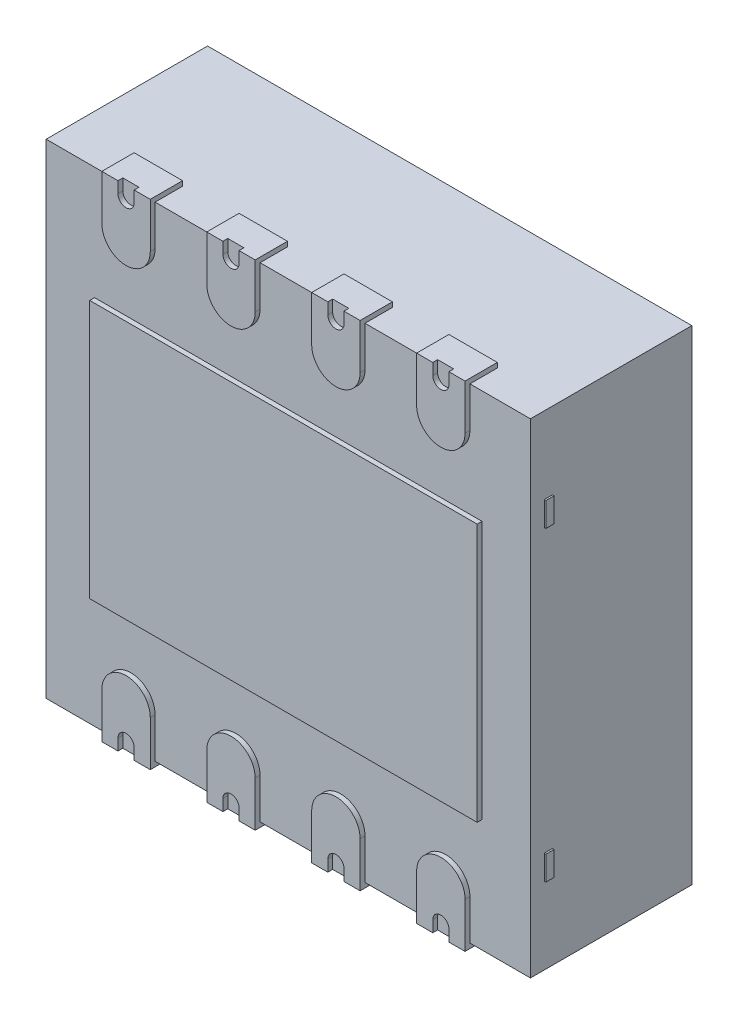
SolidWorks part; units mm, degrees
ref_plane "Front Plane" through (0, 0, 0) normal (0, 0, 1) x (1, 0, 0)
ref_plane "Top Plane" through (0, 0, 0) normal (0, 1, 0) x (1, 0, 0)
ref_plane "Right Plane" through (0, 0, 0) normal (1, 0, 0) x (0, 0, -1)
sketch "Sketch1" plane through (0, 0, 0) normal (0, 0, 1) x (1, 0, 0)
  line L1 (1.5, 1.5) -> (-1.5, 1.5)
  line L2 (1.5, 1.5) -> (1.5, -1.5)
  line L3 (1.5, -1.5) -> (-1.5, -1.5)
  line L4 (-1.5, 1.5) -> (-1.5, -1.5)
  line L5 (1.5, 1.5) -> (-1.5, -1.5) construction
  line L6 (1.5, -1.5) -> (-1.5, 1.5) construction
  point P0 (0, 0)
  dimension "D1" = 3
  dimension "D2" = 3
extrude "Boss-Extrude1" add sketch "Sketch1" against normal blind 1
sketch "Sketch2" plane through (0, 0, 0) normal (0, 0, 1) x (-1, 0, 0)
  line L0 (-0.975, 1.25) -> (-0.975, 1.6035) construction
  line L1 (1.2, 0.8) -> (-1.2, 0.8)
  line L2 (1.2, 0.8) -> (1.2, -0.8)
  line L3 (1.2, -0.8) -> (-1.2, -0.8)
  line L4 (-1.2, 0.8) -> (-1.2, -0.8)
  line L5 (1.2, 0.8) -> (-1.2, -0.8) construction
  line L6 (1.2, -0.8) -> (-1.2, 0.8) construction
  line L7 (-1.125, 1.25) -> (-1.125, 1.6035)
  line L8 (-0.825, 1.25) -> (-0.825, 1.6035)
  line L9 (1.5, 1.5) -> (-1.5, 1.5) construction
  line L10 (-0.175, 1.25) -> (-0.175, 1.6035)
  line L11 (-0.475, 1.25) -> (-0.475, 1.6035)
  line L12 (-0.325, 1.25) -> (-0.325, 1.6035) construction
  line L13 (0.475, 1.25) -> (0.475, 1.6035)
  line L14 (0.175, 1.25) -> (0.175, 1.6035)
  line L15 (0.325, 1.25) -> (0.325, 1.6035) construction
  line L16 (1.125, 1.25) -> (1.125, 1.6035)
  line L17 (0.825, 1.25) -> (0.825, 1.6035)
  line L18 (0.975, 1.25) -> (0.975, 1.6035) construction
  line L19 (0, 0) -> (0.825, 0) construction
  line L20 (-0.975, -1.25) -> (-0.975, -1.6035) construction
  line L21 (-1.125, -1.25) -> (-1.125, -1.6035)
  line L22 (-0.825, -1.25) -> (-0.825, -1.6035)
  line L23 (-0.325, -1.25) -> (-0.325, -1.6035) construction
  line L24 (-0.475, -1.25) -> (-0.475, -1.6035)
  line L25 (-0.175, -1.25) -> (-0.175, -1.6035)
  line L26 (0.325, -1.25) -> (0.325, -1.6035) construction
  line L27 (0.175, -1.25) -> (0.175, -1.6035)
  line L28 (0.475, -1.25) -> (0.475, -1.6035)
  line L29 (0.975, -1.25) -> (0.975, -1.6035) construction
  line L30 (0.825, -1.25) -> (0.825, -1.6035)
  line L31 (1.125, -1.25) -> (1.125, -1.6035)
  arc A0 (-1.125, 1.25) -> (-0.825, 1.25) centre (-0.975, 1.25) ccw
  arc A1 (-0.825, 1.6035) -> (-1.125, 1.6035) centre (-0.975, 1.6035) ccw
  arc A2 (-0.475, 1.25) -> (-0.175, 1.25) centre (-0.325, 1.25) ccw
  arc A3 (-0.175, 1.6035) -> (-0.475, 1.6035) centre (-0.325, 1.6035) ccw
  arc A4 (0.175, 1.25) -> (0.475, 1.25) centre (0.325, 1.25) ccw
  arc A5 (0.475, 1.6035) -> (0.175, 1.6035) centre (0.325, 1.6035) ccw
  arc A6 (0.825, 1.25) -> (1.125, 1.25) centre (0.975, 1.25) ccw
  arc A7 (1.125, 1.6035) -> (0.825, 1.6035) centre (0.975, 1.6035) ccw
  arc A8 (-1.125, -1.25) -> (-0.825, -1.25) centre (-0.975, -1.25) cw
  arc A9 (-0.825, -1.6035) -> (-1.125, -1.6035) centre (-0.975, -1.6035) cw
  arc A10 (-0.475, -1.25) -> (-0.175, -1.25) centre (-0.325, -1.25) cw
  arc A11 (-0.175, -1.6035) -> (-0.475, -1.6035) centre (-0.325, -1.6035) cw
  arc A12 (0.175, -1.25) -> (0.475, -1.25) centre (0.325, -1.25) cw
  arc A13 (0.475, -1.6035) -> (0.175, -1.6035) centre (0.325, -1.6035) cw
  arc A14 (0.825, -1.25) -> (1.125, -1.25) centre (0.975, -1.25) cw
  arc A15 (1.125, -1.6035) -> (0.825, -1.6035) centre (0.975, -1.6035) cw
  point P0 (0, 0)
  point P8 (-0.975, 1.4268)
  point P13 (-0.975, 1.1)
  point P19 (-0.325, 1.4268)
  point P26 (0.325, 1.4268)
  point P33 (0.975, 1.4268)
  point P41 (-0.975, -1.4268)
  point P48 (-0.325, -1.4268)
  point P55 (0.325, -1.4268)
  point P62 (0.975, -1.4268)
  dimension "D1" = 1.6
  dimension "D2" = 2.4
  dimension "D3" = 0.3
  dimension "D4" = 0.4
  dimension "D5" = 0.975
  dimension "D6" = 4
extrude "Boss-Extrude2" add sketch "Sketch2" along normal blind 0.03
sketch "Sketch4" plane through (0, 0, -1) normal (0, 0, -1) x (-1, 0, 0)
  line L1 (1.5, 1.5) -> (-1.5, 1.5)
  line L2 (1.5, 1.5) -> (1.5, -1.5)
  line L3 (1.5, -1.5) -> (-1.5, -1.5)
  line L4 (-1.5, 1.5) -> (-1.5, -1.5)
  line L5 (-2.0468, 1.8988) -> (1.8937, 1.8988)
  line L6 (-2.0468, 1.8988) -> (-2.0468, -1.9448)
  line L7 (-2.0468, -1.9448) -> (1.8937, -1.9448)
  line L8 (1.8937, 1.8988) -> (1.8937, -1.9448)
extrude "Cut-Extrude1" cut sketch "Sketch4" against normal blind 60.05
sketch "Sketch7" plane through (0, -1.5, 0) normal (0, -1, 0) x (1, 0, 0)
  line L0 (0.825, 0.03) -> (0.825, 0) construction
  line L1 (1.125, -0.17) -> (0.825, -0.17)
  line L2 (1.125, -0.17) -> (1.125, 0.03)
  line L3 (1.125, 0.03) -> (0.825, 0.03)
  line L4 (0.825, -0.17) -> (0.825, 0.03)
  line L5 (0.175, 0.03) -> (0.175, 0) construction
  line L6 (0.475, -0.17) -> (0.175, -0.17)
  line L7 (0.475, -0.17) -> (0.475, 0.03)
  line L8 (0.475, 0.03) -> (0.175, 0.03)
  line L9 (0.175, -0.17) -> (0.175, 0.03)
  line L10 (-0.475, 0.03) -> (-0.475, 0) construction
  line L11 (-0.175, -0.17) -> (-0.475, -0.17)
  line L12 (-0.175, -0.17) -> (-0.175, 0.03)
  line L13 (-0.175, 0.03) -> (-0.475, 0.03)
  line L14 (-0.475, -0.17) -> (-0.475, 0.03)
  line L15 (-1.125, 0.03) -> (-1.125, 0) construction
  line L16 (-0.825, -0.17) -> (-1.125, -0.17)
  line L17 (-0.825, -0.17) -> (-0.825, 0.03)
  line L18 (-0.825, 0.03) -> (-1.125, 0.03)
  line L19 (-1.125, -0.17) -> (-1.125, 0.03)
  point P7 (0.825, 0.015)
  point P22 (-0.475, 0.015)
  dimension "D1" = 0
  dimension "D2" = 0
  dimension "D3" = 0
  dimension "D4" = 0
  dimension "D5" = 0.2
  dimension "D6" = 0.2
  dimension "D7" = 0.2
  dimension "D8" = 0.2
extrude "Boss-Extrude3" add sketch "Sketch7" along normal blind 0.03
mirror "Mirror1" about plane through (0, 0, 0) normal (0, 1, 0) of "Boss-Extrude3"
sketch "Sketch8" plane through (0, 0, 0.03) normal (0, 0, 1) x (-1, 0, 0)
  line L0 (-0.975, 1.6098) -> (-0.975, 1.4598) construction
  line L1 (-0.925, 1.6098) -> (-0.925, 1.4598)
  line L2 (-1.025, 1.6098) -> (-1.025, 1.4598)
  line L3 (-0.375, 1.6098) -> (-0.375, 1.4598)
  line L6 (-0.275, 1.6098) -> (-0.275, 1.4598)
  line L9 (-0.325, 1.6098) -> (-0.325, 1.4598) construction
  line L13 (0.275, 1.6098) -> (0.275, 1.4598)
  line L15 (0.375, 1.6098) -> (0.375, 1.4598)
  line L16 (0.325, 1.6098) -> (0.325, 1.4598) construction
  line L17 (0.925, 1.6098) -> (0.925, 1.4598)
  line L18 (1.025, 1.6098) -> (1.025, 1.4598)
  line L19 (0.975, 1.6098) -> (0.975, 1.4598) construction
  line L20 (0, 0) -> (0.4114, 0) construction
  line L21 (-0.975, -1.6098) -> (-0.975, -1.4598) construction
  line L22 (-0.925, -1.6098) -> (-0.925, -1.4598)
  line L23 (-1.025, -1.6098) -> (-1.025, -1.4598)
  line L24 (-0.325, -1.6098) -> (-0.325, -1.4598) construction
  line L25 (-0.275, -1.6098) -> (-0.275, -1.4598)
  line L26 (-0.375, -1.6098) -> (-0.375, -1.4598)
  line L27 (0.325, -1.6098) -> (0.325, -1.4598) construction
  line L28 (0.375, -1.6098) -> (0.375, -1.4598)
  line L29 (0.275, -1.6098) -> (0.275, -1.4598)
  line L30 (0.975, -1.6098) -> (0.975, -1.4598) construction
  line L31 (1.025, -1.6098) -> (1.025, -1.4598)
  line L32 (0.925, -1.6098) -> (0.925, -1.4598)
  arc A0 (-0.925, 1.6098) -> (-1.025, 1.6098) centre (-0.975, 1.6098) ccw
  arc A1 (-1.025, 1.4598) -> (-0.925, 1.4598) centre (-0.975, 1.4598) ccw
  arc A8 (-0.275, 1.6098) -> (-0.375, 1.6098) centre (-0.325, 1.6098) ccw
  arc A9 (-0.375, 1.4598) -> (-0.275, 1.4598) centre (-0.325, 1.4598) ccw
  arc A10 (0.375, 1.6098) -> (0.275, 1.6098) centre (0.325, 1.6098) ccw
  arc A11 (0.275, 1.4598) -> (0.375, 1.4598) centre (0.325, 1.4598) ccw
  arc A12 (1.025, 1.6098) -> (0.925, 1.6098) centre (0.975, 1.6098) ccw
  arc A13 (0.925, 1.4598) -> (1.025, 1.4598) centre (0.975, 1.4598) ccw
  arc A14 (-0.925, -1.6098) -> (-1.025, -1.6098) centre (-0.975, -1.6098) cw
  arc A15 (-1.025, -1.4598) -> (-0.925, -1.4598) centre (-0.975, -1.4598) cw
  arc A16 (-0.275, -1.6098) -> (-0.375, -1.6098) centre (-0.325, -1.6098) cw
  arc A17 (-0.375, -1.4598) -> (-0.275, -1.4598) centre (-0.325, -1.4598) cw
  arc A18 (0.375, -1.6098) -> (0.275, -1.6098) centre (0.325, -1.6098) cw
  arc A19 (0.275, -1.4598) -> (0.375, -1.4598) centre (0.325, -1.4598) cw
  arc A20 (1.025, -1.6098) -> (0.925, -1.6098) centre (0.975, -1.6098) cw
  arc A21 (0.925, -1.4598) -> (1.025, -1.4598) centre (0.975, -1.4598) cw
  point P2 (-0.975, 1.5348)
  point P11 (-0.325, 1.5348)
  point P18 (0.325, 1.5348)
  point P25 (0.975, 1.5348)
  point P32 (-0.975, -1.5348)
  point P40 (-0.325, -1.5348)
  point P47 (0.325, -1.5348)
  point P54 (0.975, -1.5348)
  dimension "D1" = 0.05
  dimension "D2" = 4
  dimension "D3" = 0.15
extrude "Cut-Extrude2" cut sketch "Sketch8" against normal blind 0.03
sketch "Sketch9" plane through (-1.5, 0, 0) normal (-1, 0, 0) x (0, 0, 1)
  line L0 (0, 0) -> (-0.4231, 0) construction
  line L1 (-0.0858, 1.0236) -> (-0.0858, 0.8736)
  line L2 (-0.0858, 1.0236) -> (-0.1358, 1.0236)
  line L3 (-0.1358, 1.0236) -> (-0.1358, 0.8736)
  line L4 (-0.0858, 0.8736) -> (-0.1358, 0.8736)
  line L5 (-0.0858, -0.8736) -> (-0.1358, -0.8736)
  line L6 (-0.1358, -1.0236) -> (-0.1358, -0.8736)
  line L7 (-0.0858, -1.0236) -> (-0.1358, -1.0236)
  line L8 (-0.0858, -1.0236) -> (-0.0858, -0.8736)
  dimension "D1" = 0.15
  dimension "D2" = 0.05
extrude "Boss-Extrude4" add sketch "Sketch9" along normal blind 0.01
mirror "Mirror2" about plane through (0, 0, 0) normal (1, 0, 0) of "Boss-Extrude4"
sketch "Sketch11" plane through (0, 0, -1) normal (0, 0, -1) x (-1, 0, 0)
  line L0 (70.7212, 256.2979) -> (518.7212, 256.2979) construction
  line L54 (-0.8059, 1.0381) -> (-0.4233, 0.6054)
  line L55 (-0.3623, 0.9997) -> (-0.1188, 0.9997)
  line L56 (0.473, 0.2478) -> (0.2316, 0.2478)
  line L57 (-0.4233, 1.0381) -> (-0.0972, 1.0381)
  line L58 (-0.7882, 0.654) -> (-0.7882, 0.2148)
  line L59 (-0.1188, 0.9997) -> (0.0552, 0.7211)
  line L60 (-0.0933, 0.2106) -> (-0.3961, 0.2106)
  line L61 (-0.7882, 0.2148) -> (-1.0676, 0.2148)
  line L62 (0.5173, 0.9997) -> (0.9108, 0.9942)
  line L63 (0.5012, 0.8902) -> (0.5012, 0.6704)
  line L64 (0.9437, 0.5264) -> (0.5435, 0.5264)
  line L65 (-1.0282, 0.2545) -> (-1.0282, 0.9912)
  line L66 (0.5397, 0.8504) -> (0.8294, 0.8504)
  line L67 (1.0527, 0.8482) -> (1.0507, 0.7013)
  line L68 (0.8774, 0.8024) -> (0.8774, 0.7608)
  line L69 (-1.0676, 0.2148) -> (-1.0676, 1.0381)
  line L70 (0.5435, 0.2064) -> (0.2018, 0.2064)
  line L71 (-0.1256, 0.6262) -> (-0.3623, 0.9997)
  line L72 (0.5012, 0.5594) -> (0.5012, 0.27)
  line L73 (0.2018, 1.0381) -> (0.9437, 1.0381)
  line L74 (-0.3744, 0.4818) -> (-0.3744, 0.9397)
  line L75 (0.2391, 0.6223) -> (0.473, 0.2478)
  line L76 (0.2018, 0.2064) -> (0.0526, 0.4469)
  line L77 (-0.3981, 0.2613) -> (-0.8255, 0.7578)
  line L78 (0.2887, 0.6223) -> (0.5173, 0.9997)
  line L79 (0.8742, 0.6704) -> (0.5012, 0.6704)
  line L80 (1.0877, 0.8941) -> (1.0877, 0.6704)
  line L81 (-0.3961, 0.2106) -> (-0.7882, 0.654)
  line L82 (0.0552, 0.5301) -> (-0.1126, 0.2502)
  line L83 (0.0526, 0.7966) -> (0.2018, 1.0381)
  line L84 (0.0552, 0.7211) -> (0.2223, 0.9997)
  line L85 (-0.3623, 0.2502) -> (-0.1256, 0.6262)
  line L86 (-0.3744, 0.9397) -> (-0.1788, 0.6262)
  line L87 (0.2223, 0.9997) -> (0.4653, 0.9997)
  line L88 (0.5397, 0.8504) -> (0.5397, 0.7128)
  line L89 (-0.1126, 0.2502) -> (-0.3623, 0.2502)
  line L90 (0.5397, 0.7128) -> (0.8294, 0.7128)
  line L91 (0.2316, 0.2478) -> (0.0552, 0.5301)
  line L92 (0.5012, 0.8902) -> (0.8742, 0.8902)
  line L93 (0.5435, 0.5264) -> (0.5435, 0.2064)
  line L94 (-0.8129, 0.9912) -> (-0.3744, 0.4818)
  line L95 (0.9222, 0.8422) -> (0.9222, 0.7184)
  line L96 (-0.0972, 1.0381) -> (0.0526, 0.7966)
  line L97 (0.0526, 0.4469) -> (-0.0933, 0.2106)
  line L98 (-0.8255, 0.2545) -> (-1.0282, 0.2545)
  line L99 (0.9067, 0.5594) -> (0.5012, 0.5594)
  line L100 (-1.0676, 1.0381) -> (-0.8059, 1.0381)
  line L101 (-0.1788, 0.6262) -> (-0.3981, 0.2613)
  line L102 (0.4653, 0.9997) -> (0.2391, 0.6223)
  line L103 (-0.4233, 0.6054) -> (-0.4233, 1.0381)
  line L104 (-1.0282, 0.9912) -> (-0.8129, 0.9912)
  line L105 (-0.8255, 0.7578) -> (-0.8255, 0.2545)
  line L106 (0.5012, 0.27) -> (0.2887, 0.6223)
  arc A8 (0.8742, 0.8902) -> (0.9222, 0.8422) centre (0.8742, 0.8422) cw
  arc A9 (0.9437, 1.0381) -> (1.0877, 0.8941) centre (0.9437, 0.8941) cw
  arc A10 (0.9222, 0.7184) -> (0.8742, 0.6704) centre (0.8742, 0.7184) cw
  arc A11 (1.0877, 0.6704) -> (0.9437, 0.5264) centre (0.9437, 0.6704) cw
  arc A12 (0.8294, 0.8504) -> (0.8774, 0.8024) centre (0.8294, 0.8024) cw
  arc A13 (1.0507, 0.7013) -> (0.9067, 0.5594) centre (0.9067, 0.7034) cw
  arc A14 (0.8294, 0.7128) -> (0.8774, 0.7608) centre (0.8294, 0.7608) ccw
  arc A15 (0.9108, 0.9942) -> (1.0527, 0.8482) centre (0.9087, 0.8502) cw
sketch "Sketch12" plane through (0, 0, -1) normal (0, 0, -1) x (-1, 0, 0)
  line L0 (-1.0422, -0.9486) -> (0.9798, -0.9486) construction
  text T0 "<b>TJA1448</b>" font "Century Gothic" height 0.4
extrude "Boss-Extrude9" add sketch "Sketch11" along normal blind 0.01 contours A11 L80 A9 L73 L83 L96 L57 L103 L54 L100 L69 L61 L58 L81 L60 L97 L76 L70 L93 L64 L87 L102 L75 L56 L91 L82 L89 L85 L71 L55 L59 L84 L77 L105 L98 L65 L104 L94 L74 L86 L101 L62 A15 L67 A13 L99 L72 L106 | A10 L95 A8 L92 L63 L79 A14 L90 L88 L66 A12 L68
extrude "Boss-Extrude10" add sketch "Sketch12" along normal blind 0.01
